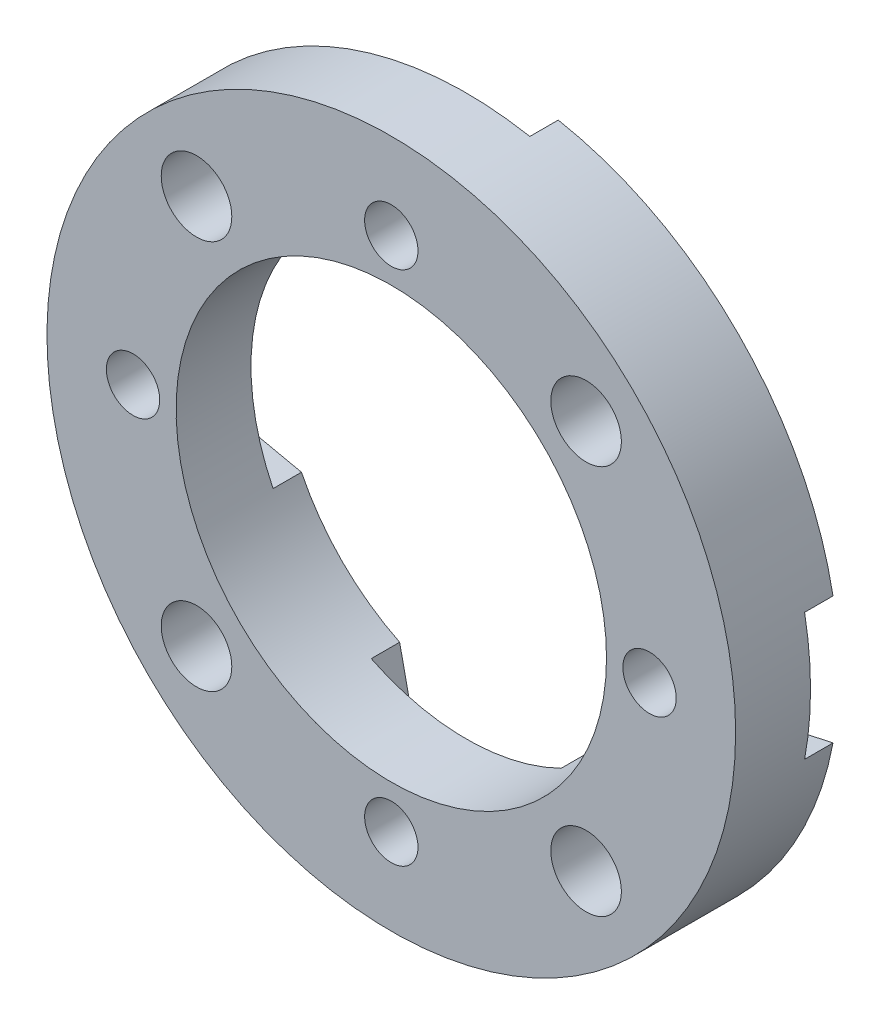
SolidWorks part; units mm, degrees
ref_plane "前视基准面" through (0, 0, 0) normal (0, 0, 1) x (1, 0, 0)
ref_plane "上视基准面" through (0, 0, 0) normal (0, 1, 0) x (1, 0, 0)
ref_plane "右视基准面" through (0, 0, 0) normal (1, 0, 0) x (0, 0, -1)
sketch "草图1" plane through (0, 0, 0) normal (0, 0, 1) x (1, 0, 0)
  line L0 (-11.3137, 11.3137) -> (0, 0) construction
  line L1 (0, 0) -> (0, 15) construction
  circle A0 centre (0, 0) radius 15 construction
  circle A1 centre (0, 0) radius 16 construction
  circle A2 centre (0, 15) radius 1.55
  circle A3 centre (15, 0) radius 1.55
  circle A4 centre (0, -15) radius 1.55
  circle A5 centre (-15, 0) radius 1.55
  circle A6 centre (-11.3137, 11.3137) radius 2.05
  circle A7 centre (11.3137, 11.3137) radius 2.05
  circle A8 centre (11.3137, -11.3137) radius 2.05
  circle A9 centre (-11.3137, -11.3137) radius 2.05
  circle A10 centre (0, 0) radius 20
  point P15 (0, 0)
  point P24 (0, 0)
  dimension "D1" = 30
  dimension "D2" = 32
  dimension "D3" = 3.1
  dimension "D6" = 4.1
  dimension "D8" = 40
  dimension "D5" = 45
  dimension "D4" = 4
  dimension "D7" = 4
extrude "凸台-拉伸1" add sketch "草图1" along normal blind 6
sketch "草图2" plane through (0, 0, 0) normal (0, 0, -1) x (-1, 0, 0)
  circle A0 centre (0, 0) radius 12.5
  dimension "D1" = 25
extrude "切除-拉伸1" cut sketch "草图2" against normal blind 31 contours A0
sketch "草图4" plane through (0, 0, 0) normal (0, 0, -1) x (-1, 0, 0)
  line L0 (-3.6972, 19.6553) -> (-5.5155, 11.2174)
  line L1 (-11.3137, 11.3137) -> (0, 0) construction
  line L2 (3.6972, 19.6553) -> (5.5155, 11.2174)
  line L3 (19.6553, -3.6972) -> (11.2174, -5.5155)
  line L4 (0, 0) -> (0, 15) construction
  line L5 (19.6553, 3.6972) -> (11.2174, 5.5155)
  line L6 (-3.6972, -19.6553) -> (-5.5155, -11.2174)
  line L7 (3.6972, -19.6553) -> (5.5155, -11.2174)
  line L8 (-19.6553, 3.6972) -> (-11.2174, 5.5155)
  line L9 (-19.6553, -3.6972) -> (-11.2174, -5.5155)
  circle A0 centre (0, 0) radius 20 construction
  circle A1 centre (0, 0) radius 12.5 construction
  arc A2 (3.6972, 19.6553) -> (-3.6972, 19.6553) centre (0, 0) ccw
  arc A3 (5.5155, 11.2174) -> (-5.5155, 11.2174) centre (0, 0) ccw
  arc A4 (11.2174, -5.5155) -> (11.2174, 5.5155) centre (0, 0) ccw
  arc A5 (19.6553, -3.6972) -> (19.6553, 3.6972) centre (0, 0) ccw
  arc A6 (-5.5155, -11.2174) -> (5.5155, -11.2174) centre (0, 0) ccw
  arc A7 (-3.6972, -19.6553) -> (3.6972, -19.6553) centre (0, 0) ccw
  arc A8 (-11.2174, 5.5155) -> (-11.2174, -5.5155) centre (0, 0) ccw
  arc A9 (-19.6553, 3.6972) -> (-19.6553, -3.6972) centre (0, 0) ccw
  point P13 (-8.3664, 8.3664)
  point P30 (0, 0)
  dimension "D1" = 4
extrude "切除-拉伸2" cut sketch "草图4" against normal blind 1.65
sketch "草图5" plane through (0, 0, 0) normal (0, 0, -1) x (-1, 0, 0)
  line L2 (3.6972, 19.6553) -> (5.5155, 11.2174)
  line L3 (11.2174, 5.5155) -> (19.6553, 3.6972)
  line L4 (3.6972, 19.6553) -> (5.5155, 11.2174)
  line L5 (11.2174, 5.5155) -> (19.6553, 3.6972)
  arc A2 (19.6553, 3.6972) -> (3.6972, 19.6553) centre (0, 0) ccw
  arc A3 (11.2174, 5.5155) -> (5.5155, 11.2174) centre (0, 0) ccw
  arc A4 (19.6553, 3.6972) -> (3.6972, 19.6553) centre (0, 0) ccw
  arc A5 (11.2174, 5.5155) -> (5.5155, 11.2174) centre (0, 0) ccw
  dimension "D1" = 0
extrude "切除-拉伸3" cut sketch "草图5" against normal blind 1.65
